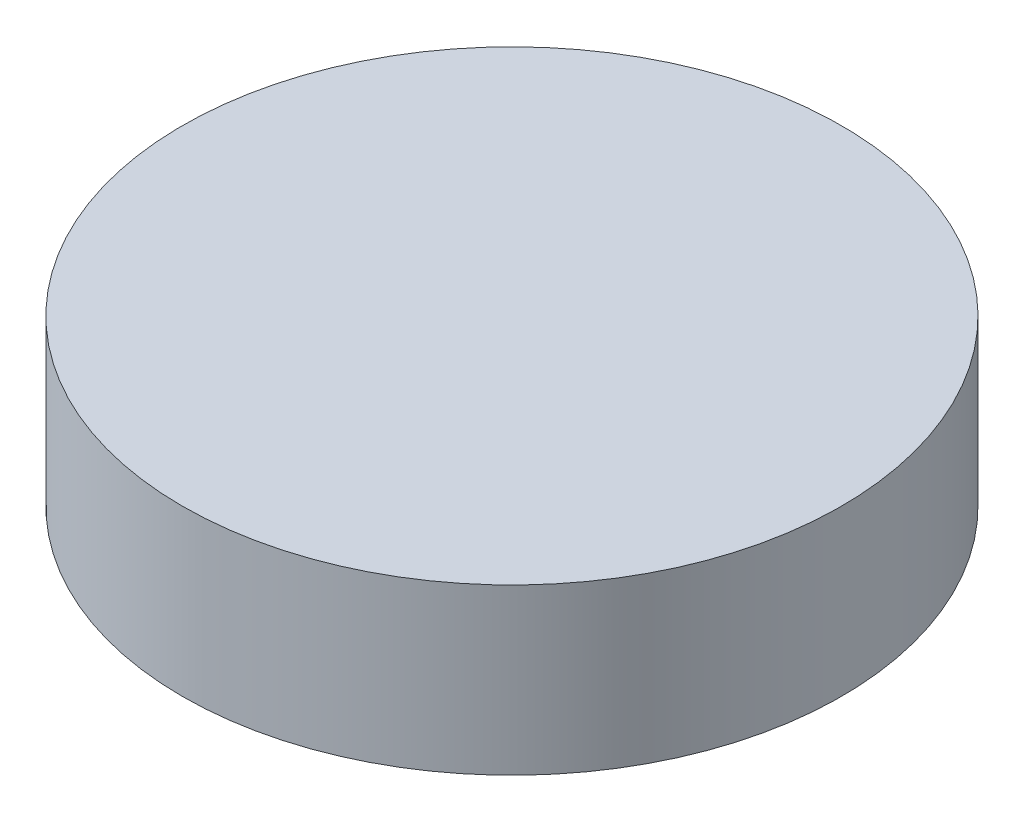
SolidWorks part; units mm, degrees
material "AISI 304"
ref_plane "Front Plane" through (0, 0, 0) normal (0, 0, 1) x (1, 0, 0)
ref_plane "Top Plane" through (0, 0, 0) normal (0, 1, 0) x (1, 0, 0)
ref_plane "Right Plane" through (0, 0, 0) normal (1, 0, 0) x (0, 0, -1)
sketch "Sketch1" plane through (0, 0, 0) normal (0, 1, 0) x (1, 0, 0)
  circle A0 centre (0, 0) radius 10
  dimension "D1" = 20
extrude "Boss-Extrude1" add sketch "Sketch1" along normal blind 5
sketch "Sketch2" plane through (0, 0, 0) normal (0, -1, 0) x (1, 0, 0)
  circle A0 centre (0, 0) radius 7.65
  dimension "D1" = 15.3
extrude "Cut-Extrude1" cut sketch "Sketch2" against normal blind 3
sketch "Sketch3" plane through (0, 0, 0) normal (1, 0, 0) x (0, 0, -1)
  line L0 (5.245, 0.8485) -> (0, 4)
  line L3 (-5.245, 0.8485) -> (5.245, 0.8485)
  line L6 (0, 0.8485) -> (0, 0) construction
  line L7 (0, 2.75) -> (0, -2.75) construction
  line L8 (0, 4) -> (-5.245, 0.8485)
  line L9 (-10, 0) -> (10, 0) construction
  line L10 (0, 4) -> (0, 0)
  dimension "D1" = 10.49
  dimension "D2" = 118
  dimension "D3" = 4
revolve "Cut-Revolve1" [suppressed] cut sketch "Sketch3" angle 360 about L6
